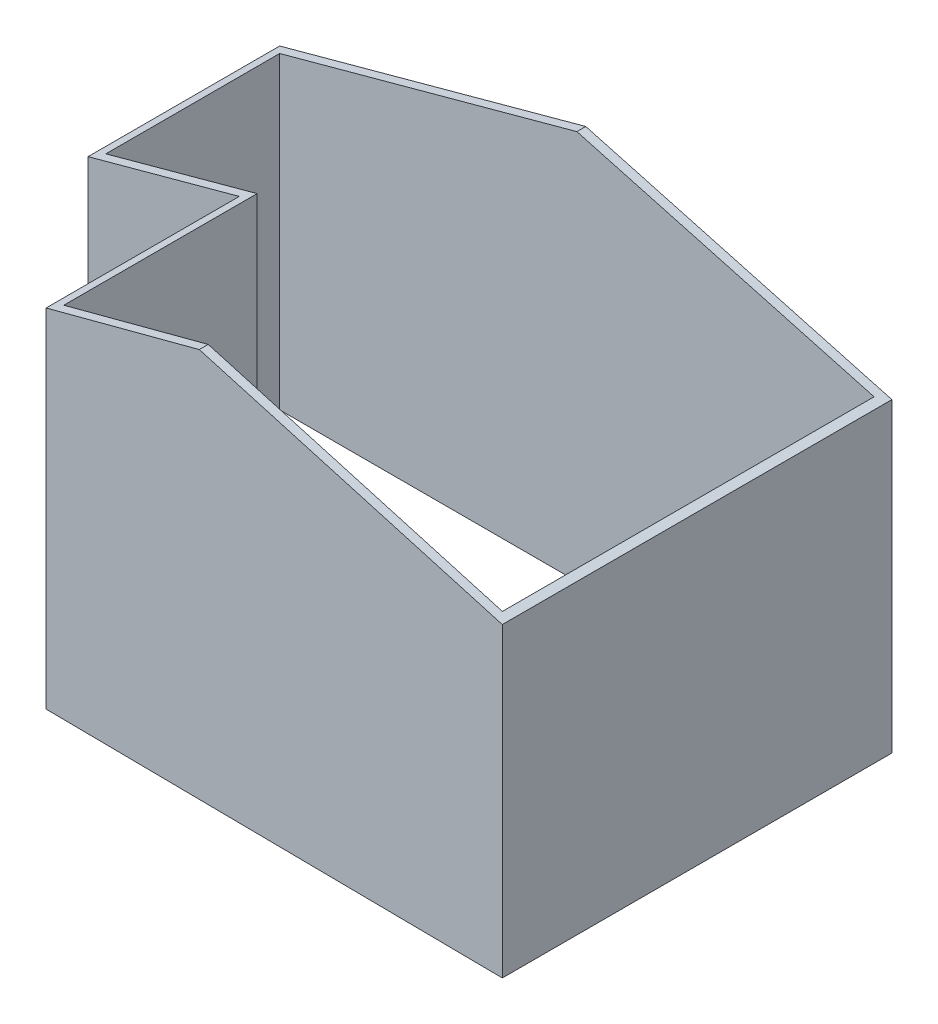
SolidWorks part; units mm, degrees
ref_plane "Front Plane" through (0, 0, 0) normal (0, 0, 1) x (1, 0, 0)
ref_plane "Top Plane" through (0, 0, 0) normal (0, 1, 0) x (1, 0, 0)
ref_plane "Right Plane" through (0, 0, 0) normal (1, 0, 0) x (0, 0, -1)
sketch "Sketch2" plane through (0, 0, 0) normal (0, 1, 0) x (1, 0, 0)
  line L0 (-63.7619, 30.8916) -> (75.9457, 30.8916)
  line L1 (75.9457, 30.8916) -> (75.9457, -58.0084)
  line L2 (75.9457, -58.0084) -> (-29.2411, -56.9254)
  line L3 (-29.2411, -56.9254) -> (-29.2411, -12.8347)
  line L4 (-29.2411, -12.8347) -> (-63.7619, -12.8347)
  line L5 (-63.7619, -12.8347) -> (-63.7619, 30.8916)
  line L6 (-61.7299, -10.8027) -> (-61.7299, 28.8596)
  line L7 (-61.7299, 28.8596) -> (73.9137, 28.8596)
  line L8 (73.9137, 28.8596) -> (73.9137, -55.9554)
  line L9 (73.9137, -55.9554) -> (-27.2091, -54.9142)
  line L10 (-27.2091, -54.9142) -> (-27.2091, -10.8027)
  line L11 (-27.2091, -10.8027) -> (-61.7299, -10.8027)
  dimension "D1" = 139.7076
  dimension "D2" = 88.9
  dimension "D3" = 2.032
extrude "Boss-Extrude1" add sketch "Sketch2" along normal blind 88.9 contours L11 L10 L9 L8 L7 L6 | L5 L0 L1 L2 L3 L4
sketch "Sketch3" plane through (0, 0, -30.8916) normal (0, 0, -1) x (-1, 0, 0)
  line L0 (-75.9457, 69.85) -> (-6.0881, 88.9)
  line L1 (-75.9457, 88.9) -> (-75.9457, 0) construction
  line L2 (63.7619, 88.9) -> (-75.9457, 88.9) construction
  line L3 (-6.0881, 88.9) -> (63.7619, 69.8747)
  line L4 (63.7619, 69.8747) -> (86.0475, 68.33)
  line L5 (86.0475, 68.33) -> (86.0475, 107.9076)
  line L6 (86.0475, 107.9076) -> (-94.4391, 107.9076)
  line L7 (-94.4391, 107.9076) -> (-94.4391, 69.85)
  line L8 (-94.4391, 69.85) -> (-75.9457, 69.85)
  line L9 (63.7619, 88.9) -> (63.7619, 0) construction
  point P11 (0, 0)
  point P14 (63.7619, 69.8747)
  dimension "D1" = 69.85
  dimension "D2" = 19.05
extrude "Cut-Extrude1" cut sketch "Sketch3" against normal blind 102.108
